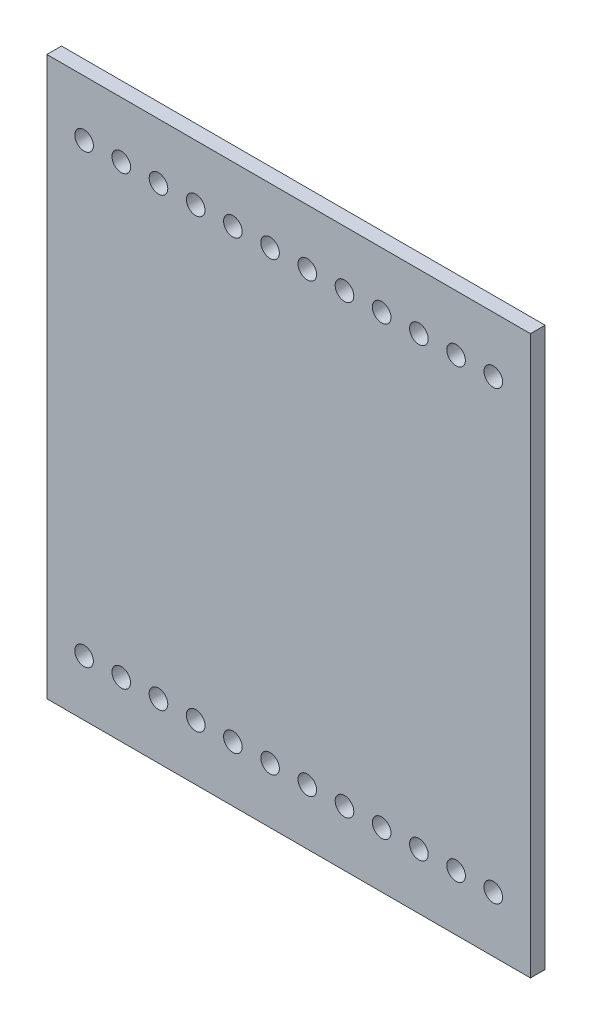
SolidWorks part; units mm, degrees
ref_plane "Alzado" through (0, 0, 0) normal (0, 0, 1) x (1, 0, 0)
ref_plane "Planta" through (0, 0, 0) normal (0, 1, 0) x (1, 0, 0)
ref_plane "Vista lateral" through (0, 0, 0) normal (1, 0, 0) x (0, 0, -1)
sketch "Croquis1" plane through (0, 0, 0) normal (0, 0, 1) x (1, 0, 0)
  line L1 (16.51, -19.05) -> (-16.51, -19.05)
  line L2 (16.51, -19.05) -> (16.51, 19.05)
  line L3 (16.51, 19.05) -> (-16.51, 19.05)
  line L4 (-16.51, -19.05) -> (-16.51, 19.05)
  line L5 (16.51, -19.05) -> (-16.51, 19.05) construction
  line L6 (16.51, 19.05) -> (-16.51, -19.05) construction
  point P0 (0, 0)
  dimension "D1" = 33.02
  dimension "D2" = 38.1
extrude "Saliente-Extruir1" add sketch "Croquis1" along normal blind 1
sketch "Croquis2" plane through (0, 0, 1) normal (0, 0, 1) x (1, 0, 0)
  line L0 (-16.51, 0) -> (16.51, 0) construction
  line L1 (-16.51, 19.05) -> (-16.51, -19.05) construction
  line L2 (16.51, -19.05) -> (16.51, 19.05) construction
  line L3 (0, -15.24) -> (0, 15.24) construction
  line L4 (13.97, 15.24) -> (-13.97, 15.24) construction
  line L5 (13.97, -15.24) -> (-13.97, -15.24) construction
  circle A1 centre (-13.97, 15.24) radius 0.635
  circle A2 centre (-11.43, 15.24) radius 0.635
  circle A3 centre (-8.89, 15.24) radius 0.635
  circle A4 centre (-6.35, 15.24) radius 0.635
  circle A5 centre (-3.81, 15.24) radius 0.635
  circle A6 centre (-1.27, 15.24) radius 0.635
  circle A7 centre (1.27, 15.24) radius 0.635
  circle A8 centre (3.81, 15.24) radius 0.635
  circle A9 centre (6.35, 15.24) radius 0.635
  circle A10 centre (8.89, 15.24) radius 0.635
  circle A11 centre (11.43, 15.24) radius 0.635
  circle A12 centre (13.97, 15.24) radius 0.635
  circle A13 centre (13.97, -15.24) radius 0.635
  circle A14 centre (11.43, -15.24) radius 0.635
  circle A15 centre (8.89, -15.24) radius 0.635
  circle A16 centre (6.35, -15.24) radius 0.635
  circle A17 centre (3.81, -15.24) radius 0.635
  circle A18 centre (1.27, -15.24) radius 0.635
  circle A19 centre (-1.27, -15.24) radius 0.635
  circle A20 centre (-3.81, -15.24) radius 0.635
  circle A21 centre (-6.35, -15.24) radius 0.635
  circle A22 centre (-8.89, -15.24) radius 0.635
  circle A23 centre (-11.43, -15.24) radius 0.635
  circle A24 centre (-13.97, -15.24) radius 0.635
  point P10 (0, 0)
  point P13 (0, 15.24)
  point P59 (0, -15.24)
  dimension "D2" = 1.27
  dimension "D4" = 2.54
  dimension "D1" = 30.48
  dimension "D3" = 12
extrude "Cortar-Extruir1" cut sketch "Croquis2" against normal through all
